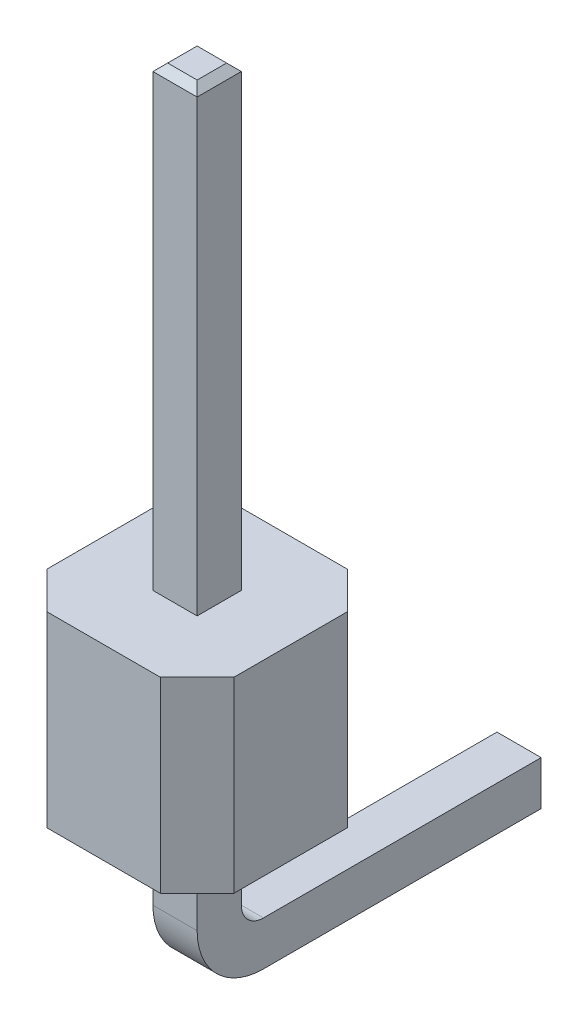
SolidWorks part; units mm, degrees
ref_plane "Front Plane" through (0, 0, 0) normal (0, 0, 1) x (1, 0, 0)
ref_plane "Top Plane" through (0, 0, 0) normal (0, 1, 0) x (1, 0, 0)
ref_plane "Right Plane" through (0, 0, 0) normal (1, 0, 0) x (0, 0, -1)
sketch "Sketch2" plane through (0, 0, 0) normal (1, 0, 0) x (0, -1, 0)
  line L0 (0.3, 3.2) -> (-0.3, 3.2)
  line L9 (-0.6, -1.27) -> (-10.5, -1.27) construction
  line L10 (0, 3.2) -> (0, -0.67) construction
  line L11 (-10.5, -1.57) -> (-10.5, -0.97)
  line L13 (-0.6, -0.97) -> (-10.5, -0.97)
  line L14 (-0.3, 3.2) -> (-0.3, -0.67)
  line L15 (-0.6, -1.57) -> (-10.5, -1.57)
  line L16 (0.3, 3.2) -> (0.3, -0.67)
  arc A3 (0, -0.67) -> (-0.6, -1.27) centre (-0.6, -0.67) cw construction
  arc A4 (-0.3, -0.67) -> (-0.6, -0.97) centre (-0.6, -0.67) cw
  arc A5 (0.3, -0.67) -> (-0.6, -1.57) centre (-0.6, -0.67) cw
  point P0 (-4.3, -1.27)
  dimension "D1" = 0.6
  dimension "D4" = 6.2
  dimension "D5" = 3.2
  dimension "D6" = 10.8
  dimension "D7" = 1.27
  dimension "D8" = 0.6
  dimension "D2" = 0.3
  dimension "D3" = 0.3
extrude "Contact" add sketch "Sketch2" along normal mid plane 0.6
chamfer "Chamfer1" distance 0.1 angle 45 8 edges at (0, -0.3, -3.2) (0.3, 0, -3.2) (0, 0.3, -3.2) (-0.3, 0, -3.2) (0, 10.5, 0.97) (0.3, 10.5, 1.27) (0, 10.5, 1.57) (-0.3, 10.5, 1.27)
ref_plane "Плоскость1" through (0, 4.3, 0) normal (0, 1, 0) x (1, 0, 0)
sketch "Sketch1" plane through (0, 4.3, 0) normal (0, 1, 0) x (0, 0, -1)
  line L0 (0, 0) -> (-1.27, 0) construction
  line L5 (-1.27, 0) -> (-1.27, 1.27) construction
  line L6 (-2.04, 1.27) -> (-0.5, 1.27)
  line L7 (-0.5, 1.27) -> (0, 0.77)
  line L8 (0, 0.77) -> (0, -0.77)
  line L9 (-2.54, 0.77) -> (-2.54, -0.77)
  line L10 (-2.04, 1.27) -> (-2.54, 0.77)
  line L11 (-0.5, -1.27) -> (0, -0.77)
  line L12 (-2.04, -1.27) -> (-0.5, -1.27)
  line L13 (-2.04, -1.27) -> (-2.54, -0.77)
  point P13 (-2.54, 0)
  dimension "D1" = 1.27
  dimension "D2" = 45
  dimension "D3" = 0.5
extrude "Plastic" add sketch "Sketch1" against normal blind 2.54
